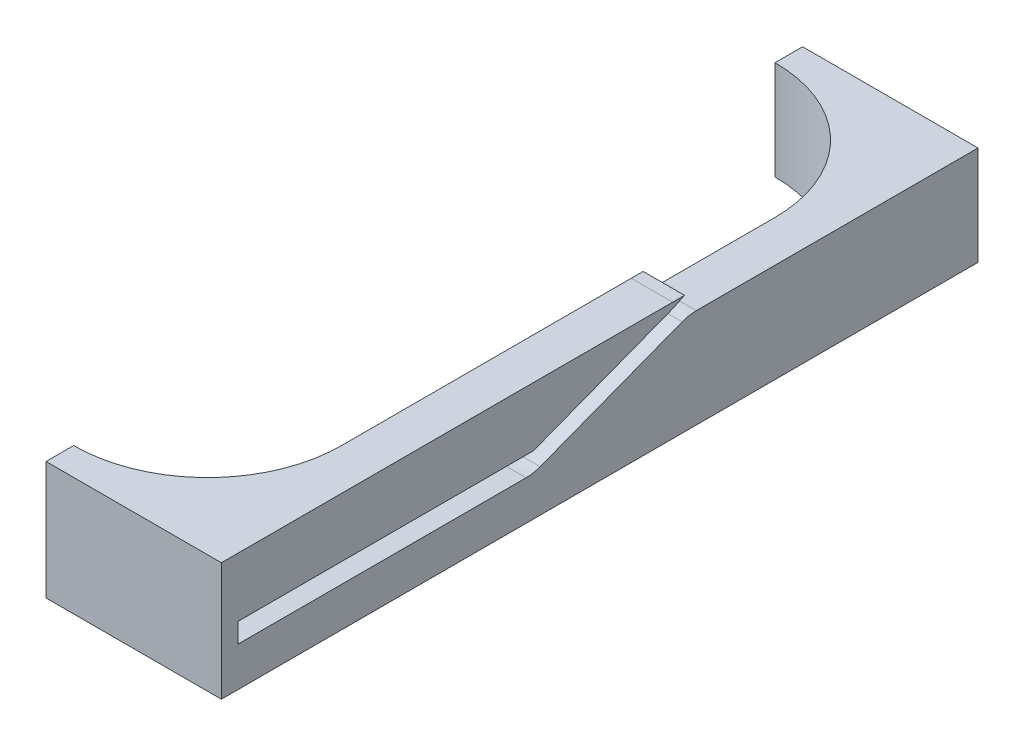
SolidWorks part; units mm, degrees
material "ABS PC"
ref_plane "Front Plane" through (0, 0, 0) normal (0, 0, 1) x (1, 0, 0)
ref_plane "Top Plane" through (0, 0, 0) normal (0, 1, 0) x (1, 0, 0)
ref_plane "Right Plane" through (0, 0, 0) normal (1, 0, 0) x (0, 0, -1)
sketch "Sketch1" plane through (0, 0, 0) normal (0, 1, 0) x (1, 0, 0)
  line L0 (-10.5, -34.9563) -> (-10.5, 75.0437) construction
  line L1 (-55, -75.9563) -> (34, -75.9563)
  line L2 (-55, -75.9563) -> (-55, 116.0437)
  line L3 (-55, 116.0437) -> (34, 116.0437)
  line L4 (34, -75.9563) -> (34, 116.0437)
  line L5 (-44.5, -34.9563) -> (-44.5, 75.0437)
  line L6 (23.5, -34.9563) -> (23.5, 75.0437)
  arc A0 (-44.5, -34.9563) -> (23.5, -34.9563) centre (-10.5, -34.9563) ccw
  arc A1 (23.5, 75.0437) -> (-44.5, 75.0437) centre (-10.5, 75.0437) ccw
  point P6 (-10.5, 20.0437)
  dimension "D3" = 10.5
  dimension "D4" = 41
  dimension "D1" = 34
  dimension "D2" = 41
  dimension "D6" = 10.5
extrude "Boss-Extrude1" add sketch "Sketch1" along normal blind 30
sketch "Sketch2" plane through (0, 0, 0) normal (0, -1, 0) x (1, 0, 0)
  circle A0 centre (-10.5, 37.8388) radius 34.9994
extrude "Cut-Extrude1" cut sketch "Sketch2" against normal blind 10
sketch "Sketch3" plane through (34, 0, 0) normal (1, 0, 0) x (0, 0, -1)
  line L0 (-75.9563, 0) -> (116.0437, 0) construction
  line L1 (-71.7863, 10) -> (3.2137, 10)
  line L2 (-71.7863, 10) -> (-71.7863, 15)
  line L3 (-71.7863, 15) -> (3.2137, 15)
  line L4 (3.2137, 10) -> (3.2137, 15)
  dimension "D1" = 5
  dimension "D2" = 10
  dimension "D3" = 75
extrude "Cut-Extrude2" cut sketch "Sketch3" against normal blind 102
sketch "Sketch4" plane through (-55, 0, 0) normal (-1, 0, 0) x (0, 0, 1)
  line L1 (-40.9707, 29.4694) -> (-41.2116, 24.5617)
  line L4 (-40.9707, 29.4694) -> (-3.2137, 15)
  line L5 (-3.2137, 15) -> (-3.2137, 10)
  line L6 (-3.2137, 10) -> (-41.2116, 24.5617)
extrude "Cut-Extrude4" cut sketch "Sketch4" against normal blind 102
sketch "Sketch6" plane through (0, 30, 0) normal (0, 1, 0) x (1, 0, 0)
  line L0 (-44.5, 75.0437) -> (-44.5, -34.9563) construction
  line L1 (-55, 42.5706) -> (-44.5, 42.5706)
  line L2 (-55, 42.5706) -> (-55, 38.5706)
  line L3 (-55, 38.5706) -> (-44.5, 38.5706)
  line L4 (-44.5, 42.5706) -> (-44.5, 38.5706)
  line L7 (23.5, 42.5706) -> (23.5, 38.5706)
  line L8 (34, 38.5706) -> (23.5, 38.5706)
  line L9 (34, 42.5706) -> (34, 38.5706)
  line L10 (34, 42.5706) -> (23.5, 42.5706)
  dimension "D1" = 4
extrude "Cut-Extrude7" cut sketch "Sketch6" against normal blind 8
sketch "Sketch7" plane through (-55, 0, 0) normal (-1, 0, 0) x (0, 0, 1)
  line L0 (-38.5706, 23.5496) -> (-42.5706, 25.0825)
  line L1 (-42.5706, 22) -> (-42.5706, 30) construction
  line L2 (-42.5706, 25.0825) -> (-42.5706, 22)
  line L3 (-42.5706, 22) -> (-38.5706, 22)
  line L4 (-38.5706, 22) -> (-38.5706, 23.5496)
extrude "Boss-Extrude2" add sketch "Sketch7" against normal up to surface (10.5 mm away) up to face at (-44.5, 16.3944, -28.5016)
sketch "Sketch8" plane through (-55, 0, 0) normal (-1, 0, 0) x (0, 0, 1)
  line L0 (-42.5706, 25.0825) -> (-55.4025, 30)
  line L1 (-116.0437, 30) -> (-42.5706, 30) construction
  line L2 (-55.4025, 30) -> (-42.5706, 30)
  line L3 (-42.5706, 30) -> (-42.5706, 25.0825)
extrude "Cut-Extrude8" cut sketch "Sketch8" against normal blind 20.7678
sketch "Sketch9" plane through (34, 0, 0) normal (1, 0, 0) x (0, 0, -1)
  line L0 (38.5706, 23.5496) -> (42.5706, 25.0825)
  line L1 (42.5706, 22) -> (42.5706, 30) construction
  line L2 (42.5706, 25.0825) -> (42.5706, 22)
  line L3 (42.5706, 22) -> (38.5706, 22)
  line L4 (38.5706, 22) -> (38.5706, 23.5496)
extrude "Boss-Extrude3" add sketch "Sketch9" against normal up to surface (10.5 mm away) up to face at (23.5, 16.3944, -28.5016)
sketch "Sketch10" plane through (34, 0, 0) normal (1, 0, 0) x (0, 0, -1)
  line L0 (42.5706, 25.0825) -> (55.4025, 30)
  line L1 (42.5706, 30) -> (116.0437, 30) construction
  line L2 (55.4025, 30) -> (42.5706, 30)
  line L3 (42.5706, 30) -> (42.5706, 25.0825)
extrude "Cut-Extrude9" cut sketch "Sketch10" against normal blind 22.8125
sketch "Sketch11" plane through (34, 0, 0) normal (1, 0, 0) x (0, 0, -1)
  line L0 (38.5706, 28.5496) -> (41.5706, 30.0071)
  line L1 (41.5706, 30.0071) -> (38.5706, 30)
  line L4 (38.5706, 30) -> (38.5706, 28.5496)
  point P3 (55.4025, 30)
  dimension "D1" = 3
sketch "Sketch12" plane through (-55, 0, 0) normal (-1, 0, 0) x (0, 0, 1)
  line L0 (-38.5706, 30) -> (-41.5706, 30)
  line L1 (-41.5706, 30) -> (-38.5706, 28.5496)
  line L2 (-38.5706, 28.5496) -> (-38.5706, 30)
  point P3 (-55.4025, 30)
  dimension "D1" = 3
extrude "Boss-Extrude6" add sketch "Sketch12" against normal up to surface (10.5 mm away) up to face at (-44.5, 23.7099, -2.0885)
extrude "Boss-Extrude7" add sketch "Sketch11" against normal up to surface (10.5 mm away) up to face at (23.5, 13.3333, -24.9391)
fillet "Fillet1" radius 10 1 edges at (-49.75, 30, -55.4025)
fillet "Fillet2" radius 10 1 edges at (28.75, 30, -55.4025)
fillet "Fillet3" radius 10 1 edges at (-49.75, 10, -3.2137)
fillet "Fillet4" radius 10 1 edges at (28.75, 10, -3.2137)
sketch "Sketch14" plane through (34, 0, 0) normal (1, 0, 0) x (0, 0, -1)
  line L0 (42.7174, 25.1388) -> (116.0437, 25.1388)
  line L1 (53.6745, 29.3378) -> (4.9417, 10.6622) construction
  line L2 (116.0437, 30) -> (116.0437, 0) construction
  line L3 (42.7174, 25.1388) -> (53.6745, 29.3378)
  line L4 (53.6745, 29.3378) -> (57.253, 30)
  line L5 (57.253, 30) -> (116.0437, 30)
  line L6 (116.0437, 30) -> (116.0437, 25.1388)
extrude "Cut-Extrude11" cut sketch "Sketch14" against normal blind 99
sketch "Sketch15" plane through (34, 0, 0) normal (1, 0, 0) x (0, 0, -1)
  line L1 (51.0699, 31.494) -> (58.6241, 31.494)
  line L2 (51.0699, 31.494) -> (51.0699, 28.2348)
  line L3 (51.0699, 28.2348) -> (58.6241, 28.2348)
  line L4 (58.6241, 31.494) -> (58.6241, 28.2348)
extrude "Cut-Extrude12" cut sketch "Sketch15" against normal blind 99
fillet "Fillet5" radius 10 2 edges at (-49.75, 25.1388, -42.7174) (28.75, 25.1388, -42.7174)
sketch "Sketch16" plane through (0, 0, -116.0437) normal (0, 0, -1) x (-1, 0, 0)
  line L1 (10.5, -2.5435) -> (61.9859, -2.5435)
  line L2 (10.5, -2.5435) -> (10.5, 39.2372)
  line L3 (10.5, 39.2372) -> (61.9859, 39.2372)
  line L4 (61.9859, -2.5435) -> (61.9859, 39.2372)
extrude "Cut-Extrude13" cut sketch "Sketch16" against normal blind 221
